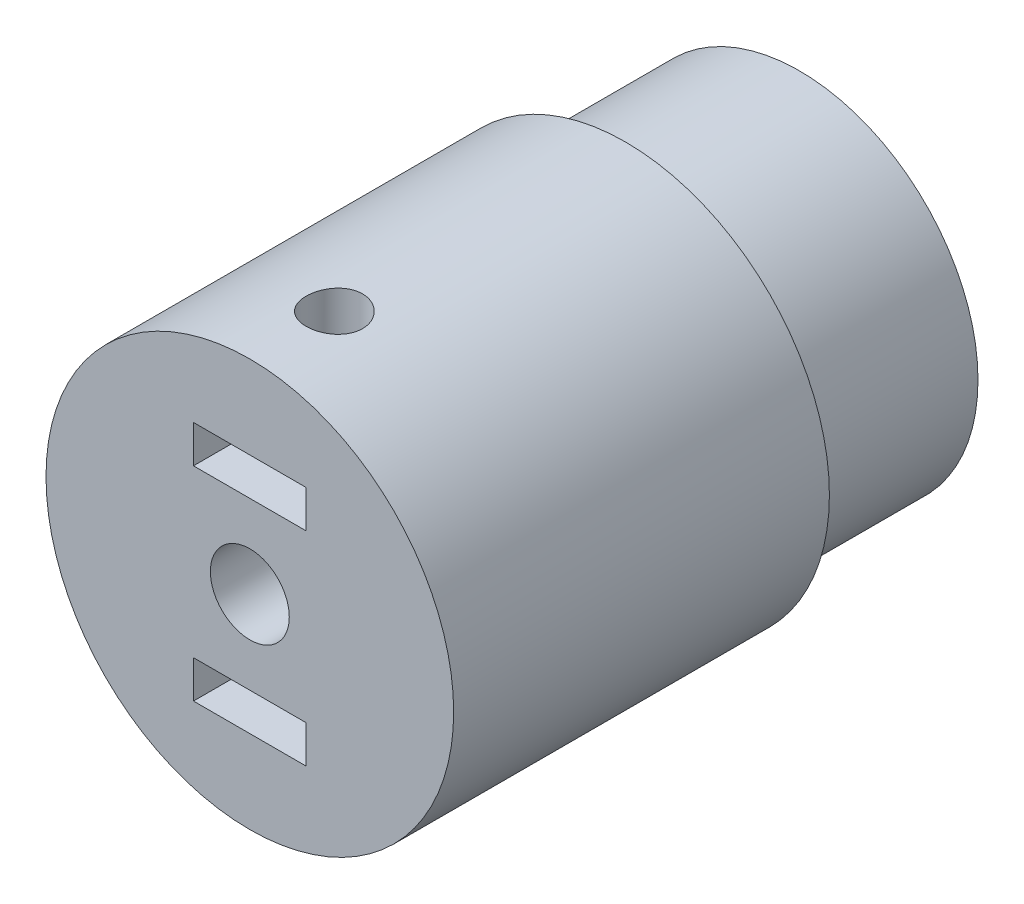
SolidWorks part; units mm, degrees
material "ABS"
ref_plane "Front Plane" through (0, 0, 0) normal (0, 0, 1) x (1, 0, 0)
ref_plane "Top Plane" through (0, 0, 0) normal (0, 1, 0) x (1, 0, 0)
ref_plane "Right Plane" through (0, 0, 0) normal (1, 0, 0) x (0, 0, -1)
sketch "Sketch1" plane through (0, 0, 0) normal (0, 0, 1) x (1, 0, 0)
  circle A0 centre (0, 0) radius 9.5
  circle A1 centre (0, 0) radius 2.1
  dimension "D1" = 19
  dimension "D2" = 4.2
extrude "Boss-Extrude1" add sketch "Sketch1" along normal blind 9.26
sketch "Sketch2" plane through (0, 0, 9.26) normal (0, 0, 1) x (1, 0, 0)
  circle A0 centre (0, 0) radius 2.1
  circle A1 centre (0, 0) radius 10.85
  circle A2 centre (0, 0) radius 2.1 construction
  dimension "D1" = 21.7
extrude "Boss-Extrude2" add sketch "Sketch2" along normal blind 20
sketch "Sketch3" plane through (0, 0, 29.26) normal (0, 0, 1) x (1, 0, 0)
  line L0 (0, 10.85) -> (0, -10.85) construction
  line L1 (-10.85, 0) -> (10.85, 0) construction
  line L2 (-3, 6.422) -> (3, 6.422)
  line L3 (-3, 6.422) -> (-3, 4.422)
  line L4 (-3, 4.422) -> (3, 4.422)
  line L5 (3, 6.422) -> (3, 4.422)
  line L6 (-3, 6.422) -> (3, 4.422) construction
  line L7 (-3, 4.422) -> (3, 6.422) construction
  line L8 (-3, -4.422) -> (3, -4.422)
  line L9 (3, -6.422) -> (3, -4.422)
  line L10 (-3, -6.422) -> (3, -6.422)
  line L11 (-3, -6.422) -> (-3, -4.422)
  circle A0 centre (0, 0) radius 10.85 construction
  point P5 (0, 5.422)
  dimension "D1" = 2
  dimension "D2" = 6
extrude "Cut-Extrude1" cut sketch "Sketch3" against normal blind 12
ref_plane "Plane1" through (0, 10.85, 0) normal (0, 1, 0) x (1, 0, 0)
sketch "Sketch4" plane through (0, 10.85, 0) normal (0, 1, 0) x (1, 0, 0)
  line L0 (-10.85, -29.26) -> (10.85, -29.26) construction
  circle A0 centre (0, -24.76) radius 1.5
  dimension "D1" = 3
  dimension "D2" = 4.5
extrude "Cut-Extrude2" cut sketch "Sketch4" against normal through all
sketch "Sketch5" plane through (0, 0, 0) normal (0, 0, -1) x (-1, 0, 0)
  line L0 (0, 9.5) -> (0, 0) construction
  line L1 (0, 0) -> (-9.5, 0) construction
  circle A0 centre (0, 0) radius 9.5 construction
  circle A1 centre (0, 0) radius 9.5 construction
  circle A3 centre (0, 6) radius 1.5
  circle A5 centre (5.1962, -3) radius 1.5
  circle A6 centre (-5.1962, -3) radius 1.5
  dimension "D1" = 3
  dimension "D2" = 6
  dimension "D3" = 3
extrude "Cut-Extrude3" cut sketch "Sketch5" against normal blind 12
